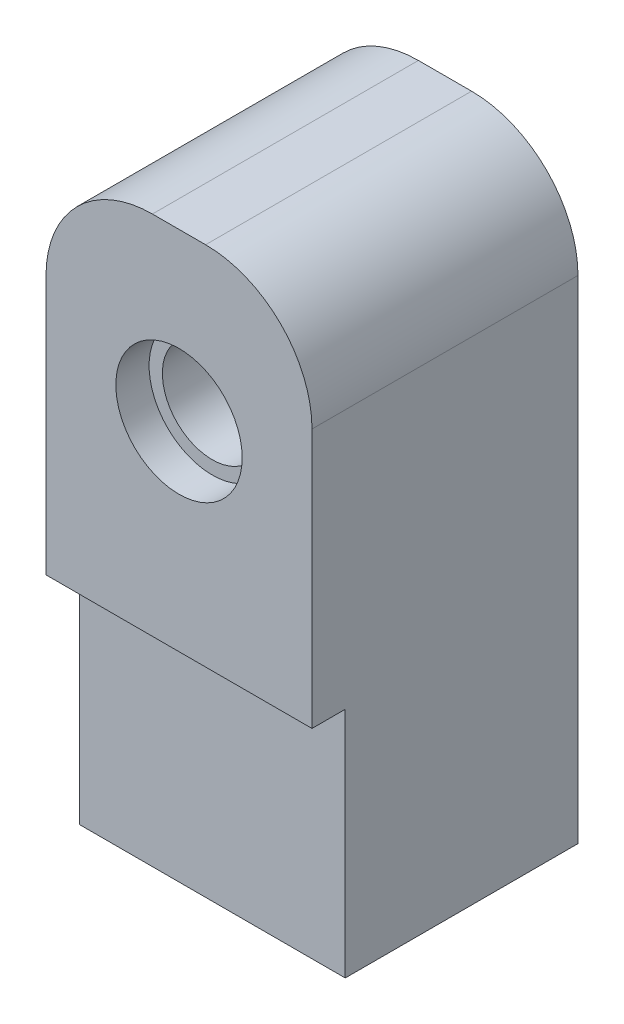
SolidWorks part; units mm, degrees
ref_plane "Front Plane" through (0, 0, 0) normal (0, 0, 1) x (1, 0, 0)
ref_plane "Top Plane" through (0, 0, 0) normal (0, 1, 0) x (1, 0, 0)
ref_plane "Right Plane" through (0, 0, 0) normal (1, 0, 0) x (0, 0, -1)
sketch "Sketch1" plane through (0, 0, 0) normal (0, 1, 0) x (1, 0, 0)
  line L1 (-0.5, 0.5) -> (0.5, 0.5)
  line L2 (-0.5, 0.5) -> (-0.5, -0.5)
  line L3 (-0.5, -0.5) -> (0.5, -0.5)
  line L4 (0.5, 0.5) -> (0.5, -0.5)
  line L5 (-0.5, 0.5) -> (0.5, -0.5) construction
  line L6 (-0.5, -0.5) -> (0.5, 0.5) construction
  point P0 (0, 0)
  dimension "D1" = 1
  dimension "D2" = 1
extrude "Boss-Extrude1" add sketch "Sketch1" along normal blind 2.25
ref_plane "Plane1" through (0, 0.875, 0) normal (0, 1, 0) x (1, 0, 0)
sketch "Sketch3" plane through (0, 0.875, 0) normal (0, 1, 0) x (1, 0, 0)
  line L0 (-0.5, -0.5) -> (-0.5, -0.375)
  line L1 (-0.5, 0.5) -> (-0.5, -0.5) construction
  line L2 (0.5, -0.5) -> (0.5, -0.375)
  line L3 (0.5, -0.5) -> (0.5, 0.5) construction
  line L4 (-0.5, -0.375) -> (0.5, -0.375)
  line L5 (-0.5, -0.5) -> (0.5, -0.5)
  dimension "D1" = 0.125
  dimension "D2" = 0.125
extrude "Cut-Extrude4" cut sketch "Sketch3" against normal blind 0.875
ref_plane "Plane2" through (0, 0, 0.5) normal (0, 0, 1) x (1, 0, 0)
sketch "Sketch5" plane through (0, 0, 0.5) normal (0, 0, 1) x (1, 0, 0)
  line L0 (0, 2.25) -> (0, 0.875) construction
  line L1 (-0.5, 2.25) -> (0.5, 2.25) construction
  line L2 (0.55, 0.875) -> (-0.55, 0.875) construction
  line L3 (0, 2.25) -> (0, 1.625) construction
  circle A0 centre (0, 1.625) radius 0.2375
  dimension "D2" = 0.475
  dimension "D1" = 0.625
extrude "Cut-Extrude5" cut sketch "Sketch5" against normal blind 0.125
ref_plane "Plane3" through (0, 0, 0.375) normal (0, 0, 1) x (1, 0, 0)
sketch "Sketch6" plane through (0, 0, 0.375) normal (0, 0, 1) x (1, 0, 0)
  circle A0 centre (0, 1.625) radius 0.1875
  dimension "D1" = 0.375
extrude "Cut-Extrude6" cut sketch "Sketch6" against normal blind 0.875
sketch "Sketch7" plane through (0, 0, 0) normal (0, 1, 0) x (1, 0, 0)
  circle A0 centre (0, 0) radius 0.25
  dimension "D1" = 0.5
extrude "Cut-Extrude7" cut sketch "Sketch7" along normal blind 1.188
fillet "Fillet1" radius 0.4 1 edges at (0.5, 2.25, 0)
fillet "Fillet2" radius 0.4 1 edges at (-0.5, 2.25, 0)
